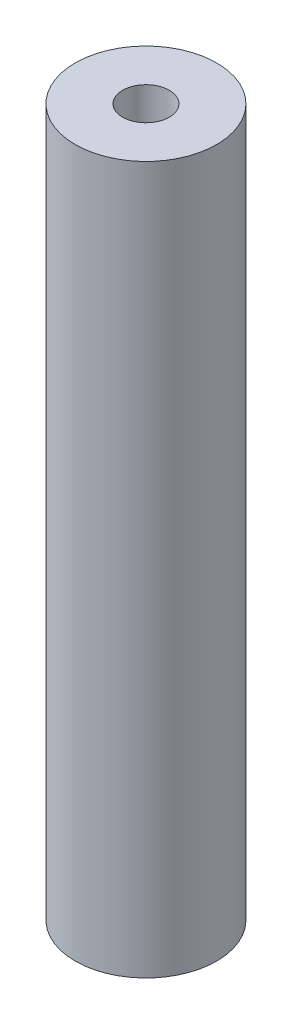
SolidWorks part; units mm, degrees
material "6061 合金"
ref_plane "前视基准面" through (0, 0, 0) normal (0, 0, 1) x (1, 0, 0)
ref_plane "上视基准面" through (0, 0, 0) normal (0, 1, 0) x (1, 0, 0)
ref_plane "右视基准面" through (0, 0, 0) normal (1, 0, 0) x (0, 0, -1)
sketch "草图1" plane through (0, 0, 0) normal (0, 1, 0) x (1, 0, 0)
  circle A0 centre (0, 0) radius 5
  dimension "D1" = 10
extrude "凸台-拉伸1" add sketch "草图1" along normal mid plane 50
hole_wizard "M4 螺纹孔1" positions "草图3" profile "草图4" tap size "M4" standard "GB"
sketch "草图3" plane through (0, 25, 0) normal (0, 1, 0) x (1, 0, 0)
  point P0 (0, 0)
sketch "草图4" plane through (0, 25, 0) normal (1, 0, 0) x (0, 0, 1)
  line L0 (0, 0) -> (0, 12.4914)
  line L1 (0, 12.4914) -> (1.65, 11.5)
  line L2 (1.65, 11.5) -> (1.65, 0)
  line L5 (1.65, 0) -> (0, 0)
  line L10 (0, 12.4914) -> (-1.65, 11.5) construction
  line L11 (0, -6.35) -> (0, 107.95) construction
  dimension "螺纹孔钻头直径" = 3.3
  dimension "螺纹孔钻头深度" = 11.5
  dimension "导头角度" = 118
mirror "镜向1" about plane through (0, 0, 0) normal (0, 1, 0) of "M4 螺纹孔1"
